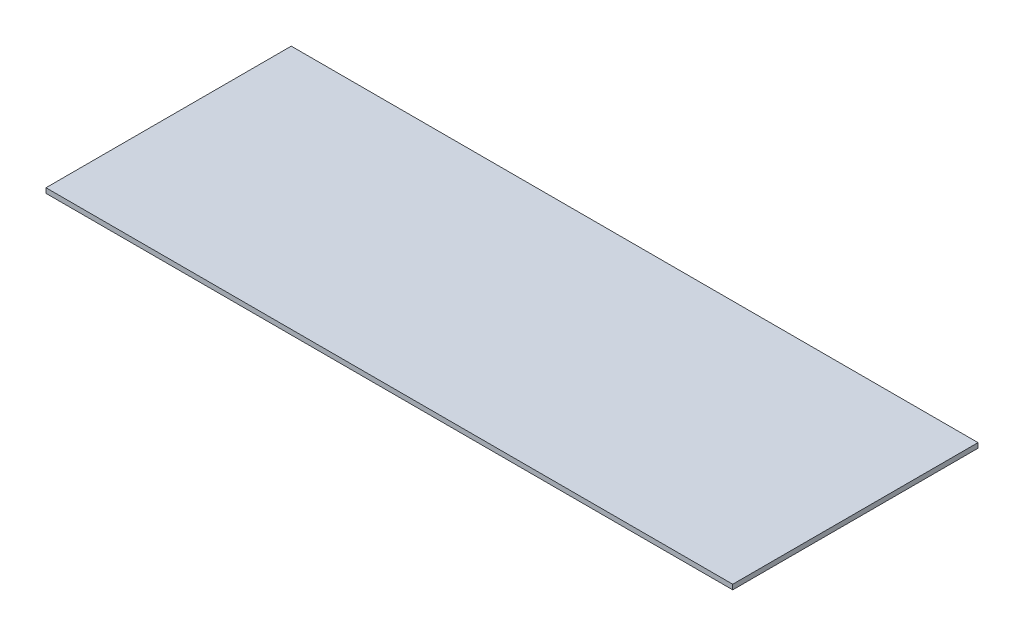
SolidWorks part; units mm, degrees
ref_plane "Alzado" through (0, 0, 0) normal (0, 0, 1) x (1, 0, 0)
ref_plane "Planta" through (0, 0, 0) normal (0, 1, 0) x (1, 0, 0)
ref_plane "Vista lateral" through (0, 0, 0) normal (1, 0, 0) x (0, 0, -1)
sketch "Croquis1" plane through (0, 0, 0) normal (0, 1, 0) x (1, 0, 0)
  line L1 (-700, 250) -> (700, 250)
  line L2 (-700, 250) -> (-700, -250)
  line L3 (-700, -250) -> (700, -250)
  line L4 (700, 250) -> (700, -250)
  line L5 (-700, 250) -> (700, -250) construction
  line L6 (-700, -250) -> (700, 250) construction
  point P0 (0, 0)
  dimension "D1" = 500
  dimension "D2" = 1400
extrude "Saliente-Extruir1" add sketch "Croquis1" along normal blind 10
